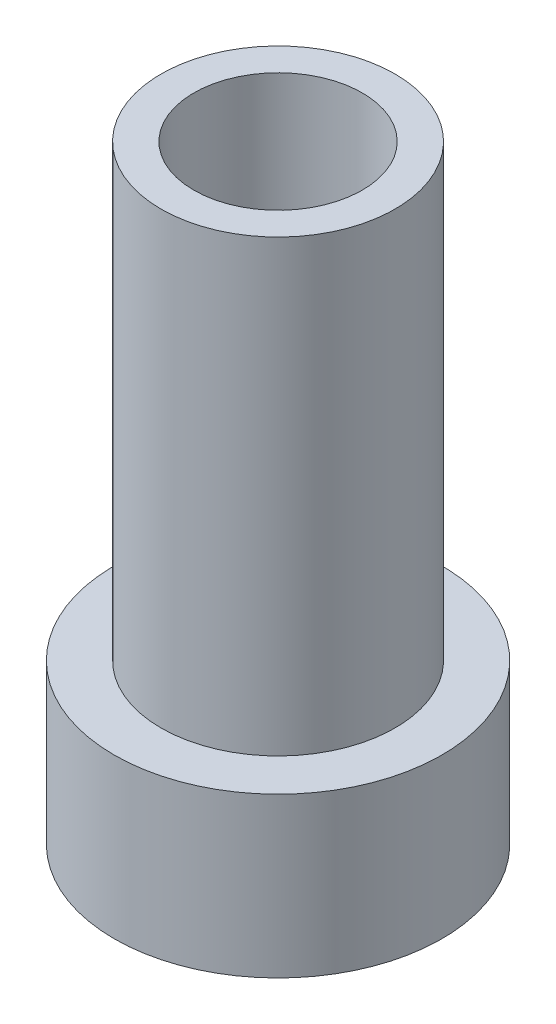
SolidWorks part; units mm, degrees
ref_plane "Front Plane" through (0, 0, 0) normal (0, 0, 1) x (1, 0, 0)
ref_plane "Top Plane" through (0, 0, 0) normal (0, 1, 0) x (1, 0, 0)
ref_plane "Right Plane" through (0, 0, 0) normal (1, 0, 0) x (0, 0, -1)
sketch "Sketch4" plane through (0, 0, 0) normal (0, 1, 0) x (1, 0, 0)
  circle A0 centre (0, 0) radius 17.5
  circle A1 centre (0, 0) radius 12.5
  dimension "D1" = 35
  dimension "D2" = 25
extrude "Boss-Extrude4" add sketch "Sketch4" against normal blind 15 and the other way blind 2.0001
sketch "Sketch13" plane through (0, 0, 0) normal (0, 1, 0) x (1, 0, 0)
  circle A0 centre (0, 0) radius 15
  dimension "D1" = 30
extrude "Cut-Extrude8" cut sketch "Sketch13" along normal blind 2
sketch "Sketch18" plane through (0, 2.0001, 0) normal (0, 1, 0) x (1, 0, 0)
  circle A0 centre (0, 0) radius 12.5
  dimension "D1" = 25
sketch "Sketch21" plane through (0, 2.0001, 0) normal (0, 1, 0) x (1, 0, 0)
  circle A0 centre (0, 0) radius 9
  circle A1 centre (0, 0) radius 12.5
  dimension "D1" = 18
extrude "Boss-Extrude10" add sketch "Sketch18" along normal blind 48 contours A0
extrude "Cut-Extrude10" cut sketch "Sketch21" along normal blind 48 contours A0
